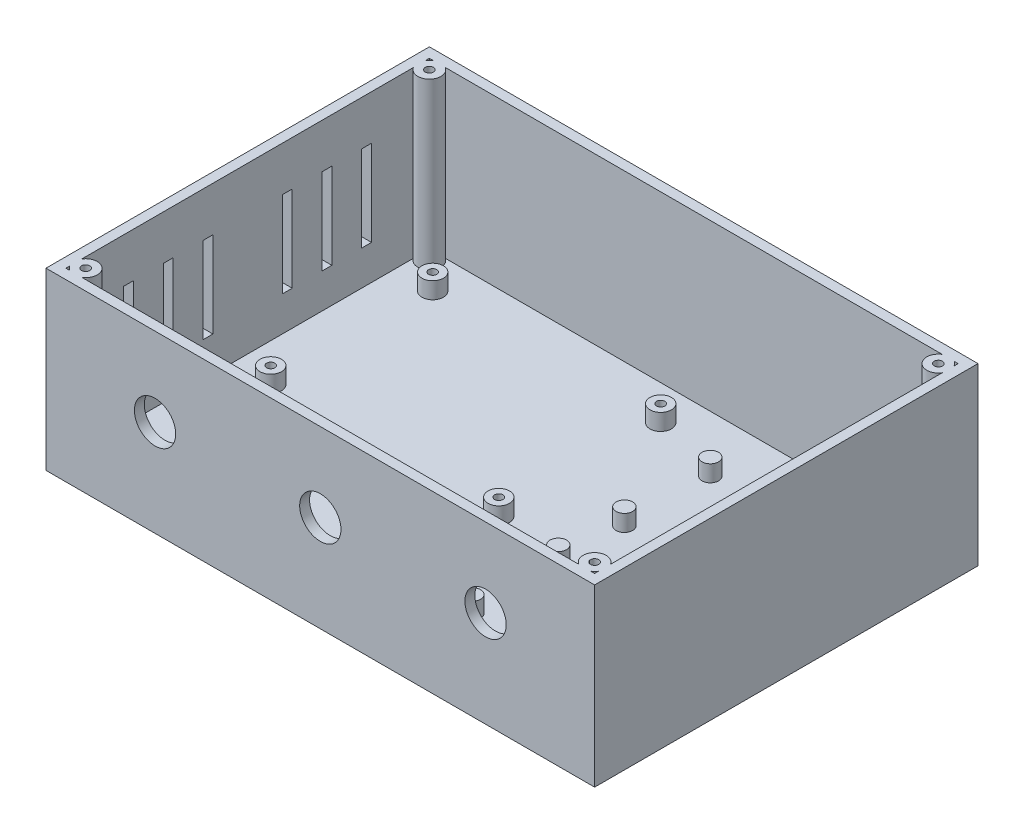
SolidWorks part; units mm, degrees
material "ABS"
ref_plane "Front Plane" through (0, 0, 0) normal (0, 0, 1) x (1, 0, 0)
ref_plane "Top Plane" through (0, 0, 0) normal (0, 1, 0) x (1, 0, 0)
ref_plane "Right Plane" through (0, 0, 0) normal (1, 0, 0) x (0, 0, -1)
other "Configuration Table"
sketch "Sketch1" plane through (0, 0, 0) normal (0, 1, 0) x (1, 0, 0)
  line L1 (-83, -58) -> (83, -58)
  line L2 (-83, -58) -> (-83, 58)
  line L3 (-83, 58) -> (83, 58)
  line L4 (83, -58) -> (83, 58)
  line L5 (-83, -58) -> (83, 58) construction
  line L6 (-83, 58) -> (83, -58) construction
extrude "Box_Solid" add sketch "Sketch1" along normal blind 53
sketch "Sketch2" plane through (0, 0, 0) normal (0, 1, 0) x (1, 0, 0)
  line L1 (-80, -55) -> (80, -55)
  line L2 (-80, -55) -> (-80, 55)
  line L3 (-80, 55) -> (80, 55)
  line L4 (80, -55) -> (80, 55)
  line L5 (-80, -55) -> (80, 55) construction
  line L6 (-80, 55) -> (80, -55) construction
extrude "Box_Cavity" cut sketch "Sketch2" along normal blind 53 from offset 3
sketch "Sketch3" plane through (0, 0, 0) normal (0, 1, 0) x (1, 0, 0)
  circle A0 centre (-77, 52) radius 3.5
  circle A1 centre (-77, -52) radius 3.5
  circle A2 centre (77, 52) radius 3.5
  circle A3 centre (77, -52) radius 3.5
extrude "Lid_Screw_Columns" add sketch "Sketch3" along normal blind 50 from offset 3
sketch "Sketch4" plane through (0, 0, 0) normal (0, 1, 0) x (1, 0, 0)
  circle A0 centre (-77, 52) radius 1.25
  circle A1 centre (-77, -52) radius 1.25
  circle A2 centre (77, 52) radius 1.25
  circle A3 centre (77, -52) radius 1.25
extrude "Lid_Screw_Holes" cut sketch "Sketch4" against normal blind 10 from offset 53
sketch "Sketch5" plane through (0, 0, 0) normal (0, 1, 0) x (1, 0, 0)
  circle A0 centre (-68.5, 44.5) radius 3.25
  circle A1 centre (-68.5, -4.5) radius 3.25
  circle A2 centre (0.5, 44.5) radius 3.25
  circle A3 centre (0.5, -4.5) radius 3.25
extrude "Relay_Bosses" add sketch "Sketch5" along normal blind 5 from offset 3
sketch "Sketch6" plane through (0, 0, 0) normal (0, 1, 0) x (1, 0, 0)
  circle A0 centre (-68.5, 44.5) radius 1.25
  circle A1 centre (-68.5, -4.5) radius 1.25
  circle A2 centre (0.5, 44.5) radius 1.25
  circle A3 centre (0.5, -4.5) radius 1.25
extrude "Relay_Boss_Holes" cut sketch "Sketch6" against normal blind 5 from offset 8
sketch "Sketch7" plane through (0, 0, 0) normal (0, 1, 0) x (1, 0, 0)
  circle A0 centre (-70.5, -20) radius 2.5
  circle A1 centre (-70.5, -42) radius 2.5
  circle A2 centre (-21.5, -20) radius 2.5
  circle A3 centre (-21.5, -42) radius 2.5
  circle A4 centre (-12, -32) radius 2.5
  circle A5 centre (-12, -44) radius 2.5
  circle A6 centre (10, -32) radius 2.5
  circle A7 centre (10, -44) radius 2.5
  circle A8 centre (22, 38) radius 2.5
  circle A9 centre (22, 12) radius 2.5
  circle A10 centre (58, 38) radius 2.5
  circle A11 centre (58, 12) radius 2.5
  circle A12 centre (22, -8) radius 2.5
  circle A13 centre (22, -34) radius 2.5
  circle A14 centre (58, -8) radius 2.5
  circle A15 centre (58, -34) radius 2.5
extrude "Board_Pads" add sketch "Sketch7" along normal blind 5 from offset 3
sketch "Sketch8" plane through (0, 0, 0) normal (0, 0, 1) x (1, 0, 0)
  circle A0 centre (-50, 29.15) radius 6.25
  circle A1 centre (0, 29.15) radius 6.25
  circle A2 centre (50, 29.15) radius 6.25
  dimension "D1" = 12.5
extrude "Cable_Gland_Holes" cut sketch "Sketch8" along normal blind 5 from offset 54
sketch "Sketch9" plane through (0, 0, 0) normal (1, 0, 0) x (0, 0, -1)
  line L1 (34.5, 13.5) -> (37.5, 13.5)
  line L2 (34.5, 13.5) -> (34.5, 39.5)
  line L3 (34.5, 39.5) -> (37.5, 39.5)
  line L4 (37.5, 13.5) -> (37.5, 39.5)
  line L5 (34.5, 13.5) -> (37.5, 39.5) construction
  line L6 (34.5, 39.5) -> (37.5, 13.5) construction
  line L7 (22.5, 13.5) -> (25.5, 13.5)
  line L8 (22.5, 13.5) -> (22.5, 39.5)
  line L9 (22.5, 39.5) -> (25.5, 39.5)
  line L10 (25.5, 13.5) -> (25.5, 39.5)
  line L11 (22.5, 13.5) -> (25.5, 39.5) construction
  line L12 (22.5, 39.5) -> (25.5, 13.5) construction
  line L13 (10.5, 13.5) -> (13.5, 13.5)
  line L14 (10.5, 13.5) -> (10.5, 39.5)
  line L15 (10.5, 39.5) -> (13.5, 39.5)
  line L16 (13.5, 13.5) -> (13.5, 39.5)
  line L17 (10.5, 13.5) -> (13.5, 39.5) construction
  line L18 (10.5, 39.5) -> (13.5, 13.5) construction
  line L19 (-13.5, 13.5) -> (-10.5, 13.5)
  line L20 (-13.5, 13.5) -> (-13.5, 39.5)
  line L21 (-13.5, 39.5) -> (-10.5, 39.5)
  line L22 (-10.5, 13.5) -> (-10.5, 39.5)
  line L23 (-13.5, 13.5) -> (-10.5, 39.5) construction
  line L24 (-13.5, 39.5) -> (-10.5, 13.5) construction
  line L25 (-25.5, 13.5) -> (-22.5, 13.5)
  line L26 (-25.5, 13.5) -> (-25.5, 39.5)
  line L27 (-25.5, 39.5) -> (-22.5, 39.5)
  line L28 (-22.5, 13.5) -> (-22.5, 39.5)
  line L29 (-25.5, 13.5) -> (-22.5, 39.5) construction
  line L30 (-25.5, 39.5) -> (-22.5, 13.5) construction
  line L31 (-37.5, 13.5) -> (-34.5, 13.5)
  line L32 (-37.5, 13.5) -> (-37.5, 39.5)
  line L33 (-37.5, 39.5) -> (-34.5, 39.5)
  line L34 (-34.5, 13.5) -> (-34.5, 39.5)
  line L35 (-37.5, 13.5) -> (-34.5, 39.5) construction
  line L36 (-37.5, 39.5) -> (-34.5, 13.5) construction
  point P0 (24, 26.5)
  point P9 (12, 26.5)
  point P14 (-12, 26.5)
  point P19 (-24, 26.5)
  point P24 (-36, 26.5)
extrude "Vent_Slots" cut sketch "Sketch9" along normal blind 5 from offset 84
sketch "Sketch10" plane through (0, 0, 0) normal (0, 1, 0) x (1, 0, 0)
  circle A0 centre (-71, 46) radius 5
  circle A1 centre (-71, -46) radius 5
  circle A2 centre (71, 46) radius 5
  circle A3 centre (71, -46) radius 5
extrude "Leg_Sockets" cut sketch "Sketch10" along normal blind 2
equation "\"box_in_L\"= 160.0   'ASSUMPTION: Enclosure inside length (PDF fallback)"
equation "\"box_in_W\"= 110.0   'ASSUMPTION: Enclosure inside width (PDF fallback)"
equation "\"box_in_H\"= 50.0   'ASSUMPTION: Enclosure inside height (PDF fallback)"
equation "\"box_wall\"= 3.0   'ASSUMPTION: Enclosure wall (designer choice)"
equation "\"gland_D\"= 12.5   'ASSUMPTION: Cable gland hole, PG7 (designer choice)"
equation "\"rly_hole_X\"= 69.0   'ASSUMPTION: Relay mounting hole spacing L (PDF fallback)"
equation "\"rly_hole_Y\"= 49.0   'ASSUMPTION: Relay mounting hole spacing W (PDF fallback)"
equation "\"D1@Box_Solid\" = \"box_in_H\" + \"box_wall\""
equation "\"D1@Sketch8\" = \"gland_D\""
